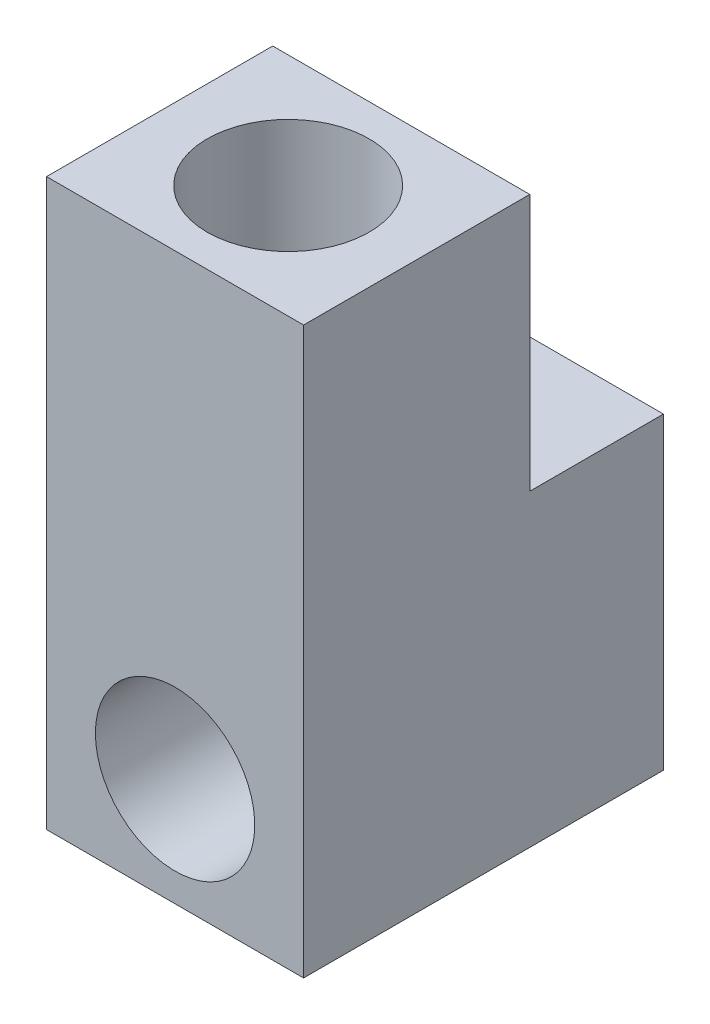
SolidWorks part; units mm, degrees
ref_plane "Спереди" through (0, 0, 0) normal (0, 0, 1) x (1, 0, 0)
ref_plane "Сверху" through (0, 0, 0) normal (0, 1, 0) x (1, 0, 0)
ref_plane "Справа" through (0, 0, 0) normal (1, 0, 0) x (0, 0, -1)
sketch "Эскиз1" plane through (0, 0, 0) normal (0, 1, 0) x (1, 0, 0)
  line L1 (-2.5, -3.5) -> (2.5, -3.5)
  line L2 (-2.5, -3.5) -> (-2.5, 3.5)
  line L3 (-2.5, 3.5) -> (2.5, 3.5)
  line L4 (2.5, -3.5) -> (2.5, 3.5)
  line L5 (-2.5, -3.5) -> (2.5, 3.5) construction
  line L6 (-2.5, 3.5) -> (2.5, -3.5) construction
  point P0 (0, 0)
  dimension "D1" = 7
  dimension "D2" = 5
extrude "Бобышка-Вытянуть1" add sketch "Эскиз1" along normal blind 11
sketch "Эскиз3" plane through (0, 11, 0) normal (0, 1, 0) x (1, 0, 0)
  line L0 (0, 0) -> (-2, 0) construction
  line L1 (0, 0) -> (0, -1.3) construction
  circle A1 centre (0, -1.3) radius 1.575
  dimension "D1" = 3.15
  dimension "D2" = 2
  dimension "D3" = 1.3
extrude "Вырез-Вытянуть1" cut sketch "Эскиз3" against normal blind 7
sketch "Эскиз4" plane through (0, 0, -3.5) normal (0, 0, -1) x (-1, 0, 0)
  line L0 (-2.5, 0) -> (2.5, 0) construction
  circle A0 centre (0, 2.1) radius 1.55
  dimension "D1" = 3.1
  dimension "D2" = 2.1
extrude "Вырез-Вытянуть2" cut sketch "Эскиз4" against normal blind 7
sketch "Эскиз5" plane through (0, 11, 0) normal (0, 1, 0) x (1, 0, 0)
  line L0 (-2.5, 3.5) -> (-2.5, 0.9)
  line L1 (-2.5, 3.5) -> (-2.5, -3.5) construction
  line L2 (2.5, 3.5) -> (-2.5, 3.5) construction
  line L3 (-2.5, 0.9) -> (2.5, 0.9)
  line L4 (2.5, -3.5) -> (2.5, 3.5) construction
  line L5 (2.5, 0.9) -> (2.5, 3.5)
  line L6 (2.5, 3.5) -> (-2.5, 3.5)
  dimension "D1" = 2.6
extrude "Вырез-Вытянуть3" cut sketch "Эскиз5" against normal blind 5
